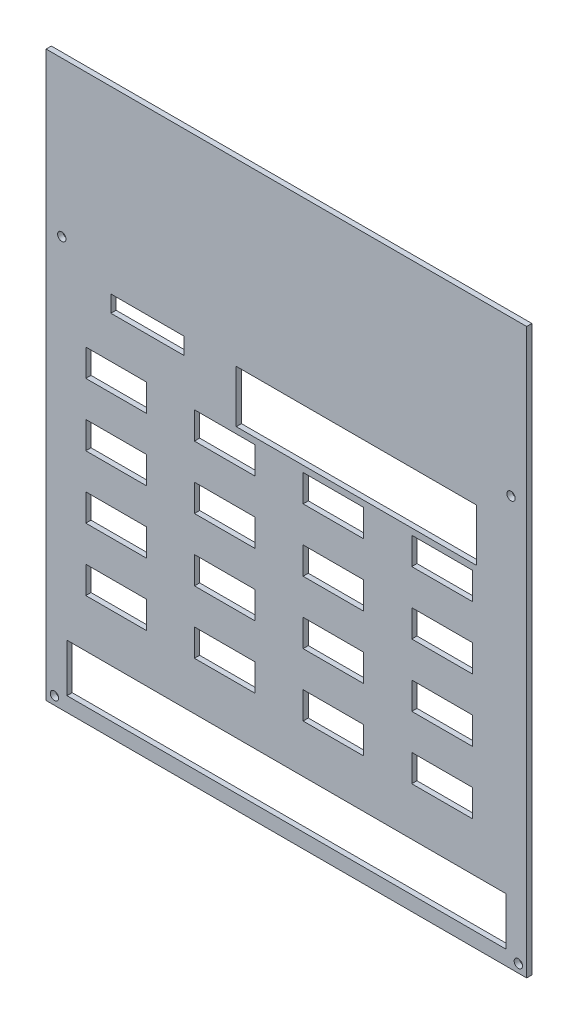
SolidWorks part; units mm, degrees
ref_plane "Plan de face" through (0, 0, 0) normal (0, 0, 1) x (1, 0, 0)
ref_plane "Plan de dessus" through (0, 0, 0) normal (0, 1, 0) x (1, 0, 0)
ref_plane "Plan de droite" through (0, 0, 0) normal (1, 0, 0) x (0, 0, -1)
sketch "Esquisse1" plane through (0, 0, 25) normal (0, 0, 1) x (1, 0, 0)
  line L1 (-217.4595, 339.4059) -> (12.5405, 339.4059)
  line L2 (-217.4595, 339.4059) -> (-217.4595, 69.4059)
  line L3 (-217.4595, 69.4059) -> (12.5405, 69.4059)
  line L4 (12.5405, 339.4059) -> (12.5405, 69.4059)
extrude "Boss.-Extru.2" add sketch "Esquisse1" along normal blind 2.5
sketch "Esquisse4" plane through (0, 0, 27.5) normal (0, 0, 1) x (1, 0, 0)
  line L0 (-217.4595, 339.4059) -> (-217.4595, 69.4059) construction
  line L1 (-207.4595, 99.4059) -> (2.5405, 99.4059)
  line L2 (-207.4595, 99.4059) -> (-207.4595, 76.4059)
  line L3 (-207.4595, 76.4059) -> (2.5405, 76.4059)
  line L4 (2.5405, 99.4059) -> (2.5405, 76.4059)
  line L5 (12.5405, 69.4059) -> (12.5405, 339.4059) construction
  line L6 (-217.4595, 69.4059) -> (12.5405, 69.4059) construction
  dimension "D1" = 10
  dimension "D2" = 10
  dimension "D3" = 7
  dimension "D4" = 23
extrude "Enlèv. mat.-Extru.1" cut sketch "Esquisse4" against normal up to next contours L4 L1 L2 L3
sketch "Esquisse5" plane through (0, 0, 27.5) normal (0, 0, 1) x (1, 0, 0)
  line L0 (-217.4595, 339.4059) -> (-217.4595, 69.4059) construction
  line L1 (-217.4595, 69.4059) -> (12.5405, 69.4059) construction
  line L2 (12.5405, 69.4059) -> (12.5405, 339.4059) construction
  circle A0 centre (-213.4595, 73.4059) radius 2
  circle A1 centre (8.5405, 73.4059) radius 2
  dimension "D1" = 4
  dimension "D3" = 4
  dimension "D2" = 4
  dimension "D4" = 4
extrude "Enlèv. mat.-Extru.2" cut sketch "Esquisse5" against normal blind 2.5
sketch "Esquisse6" plane through (0, 0, 27.5) normal (0, 0, 1) x (1, 0, 0)
  line L0 (-217.4595, 339.4059) -> (-217.4595, 69.4059) construction
  line L1 (12.5405, 339.4059) -> (-217.4595, 339.4059) construction
  line L2 (12.5405, 69.4059) -> (12.5405, 339.4059) construction
  line L4 (-186.4595, 253.4059) -> (-151.4595, 253.4059)
  line L5 (-186.4595, 253.4059) -> (-186.4595, 245.4059)
  line L6 (-186.4595, 245.4059) -> (-151.4595, 245.4059)
  line L7 (-151.4595, 253.4059) -> (-151.4595, 245.4059)
  line L8 (-126.4595, 253.4059) -> (-11.4595, 253.4059)
  line L9 (-126.4595, 253.4059) -> (-126.4595, 228.4059)
  line L10 (-126.4595, 228.4059) -> (-11.4595, 228.4059)
  line L11 (-11.4595, 253.4059) -> (-11.4595, 228.4059)
  point P18 (0, 0)
  dimension "D2" = 24
  dimension "D5" = 8
  dimension "D6" = 86
  dimension "D7" = 31
  dimension "D8" = 35
  dimension "D9" = 115
  dimension "D10" = 86
  dimension "D11" = 25
extrude "Enlèv. mat.-Extru.3" cut sketch "Esquisse6" against normal blind 2.5
sketch "Esquisse7" plane through (0, 0, 27.5) normal (0, 0, 1) x (1, 0, 0)
  line L0 (-146.4595, 225.4059) -> (-146.4595, 212.4059)
  line L1 (-198.4595, 225.4059) -> (-169.4595, 225.4059)
  line L2 (-198.4595, 225.4059) -> (-198.4595, 212.4059)
  line L3 (-198.4595, 212.4059) -> (-169.4595, 212.4059)
  line L4 (-169.4595, 225.4059) -> (-169.4595, 212.4059)
  line L5 (-146.4595, 225.4059) -> (-117.4595, 225.4059)
  line L6 (-117.4595, 225.4059) -> (-117.4595, 212.4059)
  line L7 (-146.4595, 212.4059) -> (-117.4595, 212.4059)
  line L8 (-94.4595, 225.4059) -> (-94.4595, 212.4059)
  line L9 (-94.4595, 225.4059) -> (-65.4595, 225.4059)
  line L10 (-65.4595, 225.4059) -> (-65.4595, 212.4059)
  line L11 (-94.4595, 212.4059) -> (-65.4595, 212.4059)
  line L12 (-42.4595, 225.4059) -> (-42.4595, 212.4059)
  line L13 (-42.4595, 225.4059) -> (-13.4595, 225.4059)
  line L14 (-13.4595, 225.4059) -> (-13.4595, 212.4059)
  line L15 (-42.4595, 212.4059) -> (-13.4595, 212.4059)
  line L16 (-146.4595, 195.4059) -> (-146.4595, 182.4059)
  line L17 (-146.4595, 195.4059) -> (-117.4595, 195.4059)
  line L18 (-117.4595, 195.4059) -> (-117.4595, 182.4059)
  line L19 (-146.4595, 182.4059) -> (-117.4595, 182.4059)
  line L20 (-94.4595, 195.4059) -> (-94.4595, 182.4059)
  line L21 (-94.4595, 195.4059) -> (-65.4595, 195.4059)
  line L22 (-65.4595, 195.4059) -> (-65.4595, 182.4059)
  line L23 (-94.4595, 182.4059) -> (-65.4595, 182.4059)
  line L24 (-42.4595, 195.4059) -> (-42.4595, 182.4059)
  line L25 (-42.4595, 195.4059) -> (-13.4595, 195.4059)
  line L26 (-13.4595, 195.4059) -> (-13.4595, 182.4059)
  line L27 (-42.4595, 182.4059) -> (-13.4595, 182.4059)
  line L28 (-146.4595, 165.4059) -> (-146.4595, 152.4059)
  line L29 (-146.4595, 165.4059) -> (-117.4595, 165.4059)
  line L30 (-117.4595, 165.4059) -> (-117.4595, 152.4059)
  line L31 (-146.4595, 152.4059) -> (-117.4595, 152.4059)
  line L32 (-94.4595, 165.4059) -> (-94.4595, 152.4059)
  line L33 (-94.4595, 165.4059) -> (-65.4595, 165.4059)
  line L34 (-65.4595, 165.4059) -> (-65.4595, 152.4059)
  line L35 (-94.4595, 152.4059) -> (-65.4595, 152.4059)
  line L36 (-42.4595, 165.4059) -> (-42.4595, 152.4059)
  line L37 (-42.4595, 165.4059) -> (-13.4595, 165.4059)
  line L38 (-13.4595, 165.4059) -> (-13.4595, 152.4059)
  line L39 (-42.4595, 152.4059) -> (-13.4595, 152.4059)
  line L40 (-146.4595, 135.4059) -> (-146.4595, 122.4059)
  line L41 (-146.4595, 135.4059) -> (-117.4595, 135.4059)
  line L42 (-117.4595, 135.4059) -> (-117.4595, 122.4059)
  line L43 (-146.4595, 122.4059) -> (-117.4595, 122.4059)
  line L44 (-94.4595, 135.4059) -> (-94.4595, 122.4059)
  line L45 (-94.4595, 135.4059) -> (-65.4595, 135.4059)
  line L46 (-65.4595, 135.4059) -> (-65.4595, 122.4059)
  line L47 (-94.4595, 122.4059) -> (-65.4595, 122.4059)
  line L48 (-42.4595, 135.4059) -> (-42.4595, 122.4059)
  line L49 (-42.4595, 135.4059) -> (-13.4595, 135.4059)
  line L50 (-13.4595, 135.4059) -> (-13.4595, 122.4059)
  line L51 (-42.4595, 122.4059) -> (-13.4595, 122.4059)
  line L52 (-198.4595, 195.4059) -> (-198.4595, 182.4059)
  line L53 (-198.4595, 195.4059) -> (-169.4595, 195.4059)
  line L54 (-169.4595, 195.4059) -> (-169.4595, 182.4059)
  line L55 (-198.4595, 182.4059) -> (-169.4595, 182.4059)
  line L56 (-198.4595, 165.4059) -> (-198.4595, 152.4059)
  line L57 (-198.4595, 165.4059) -> (-169.4595, 165.4059)
  line L58 (-169.4595, 165.4059) -> (-169.4595, 152.4059)
  line L59 (-198.4595, 152.4059) -> (-169.4595, 152.4059)
  line L60 (-198.4595, 135.4059) -> (-198.4595, 122.4059)
  line L61 (-198.4595, 135.4059) -> (-169.4595, 135.4059)
  line L62 (-169.4595, 135.4059) -> (-169.4595, 122.4059)
  line L63 (-198.4595, 122.4059) -> (-169.4595, 122.4059)
  line L64 (-217.4595, 339.4059) -> (-217.4595, 69.4059) construction
  line L65 (12.5405, 339.4059) -> (-217.4595, 339.4059) construction
  dimension "D1" = 13
  dimension "D2" = 29
  dimension "D3" = 114
  dimension "D4" = 19
  dimension "D5" = 4
  dimension "D6" = 4
extrude "Enlèv. mat.-Extru.4" cut sketch "Esquisse7" against normal blind 2.5
sketch "Esquisse8" plane through (0, 0, 25) normal (0, 0, -1) x (-1, 0, 0)
  line L0 (117.4595, 195.4059) -> (146.4595, 195.4059) construction
  line L1 (34.33, 200.9059) -> (194.33, 200.9059)
  line L2 (34.33, 200.9059) -> (34.33, 198.4059)
  line L3 (34.33, 198.4059) -> (194.33, 198.4059)
  line L4 (194.33, 200.9059) -> (194.33, 198.4059)
  line L5 (-12.5405, 69.4059) -> (-12.5405, 339.4059) construction
  dimension "D1" = 160
  dimension "D2" = 2.5
  dimension "D3" = 3
  dimension "D4" = 46.8705
extrude "Boss.-Extru.3" add sketch "Esquisse8" along normal blind 8
sketch "Esquisse9" plane through (0, 0, 27.5) normal (0, 0, 1) x (1, 0, 0)
  line L0 (-217.4595, 339.4059) -> (-217.4595, 69.4059) construction
  line L1 (12.5405, 339.4059) -> (-217.4595, 339.4059) construction
  circle A0 centre (-209.9595, 265.4059) radius 2
  dimension "D1" = 7.5
  dimension "D2" = 74
extrude "Enlèv. mat.-Extru.5" cut sketch "Esquisse9" against normal through all
sketch "Esquisse11" plane through (0, 0, 27.5) normal (0, 0, 1) x (1, 0, 0)
  line L0 (12.5405, 339.4059) -> (-217.4595, 339.4059) construction
  line L1 (12.5405, 69.4059) -> (12.5405, 339.4059) construction
  circle A0 centre (5.0405, 265.4059) radius 2
  dimension "D1" = 74
  dimension "D2" = 7.5
extrude "Enlèv. mat.-Extru.6" cut sketch "Esquisse11" against normal through all
